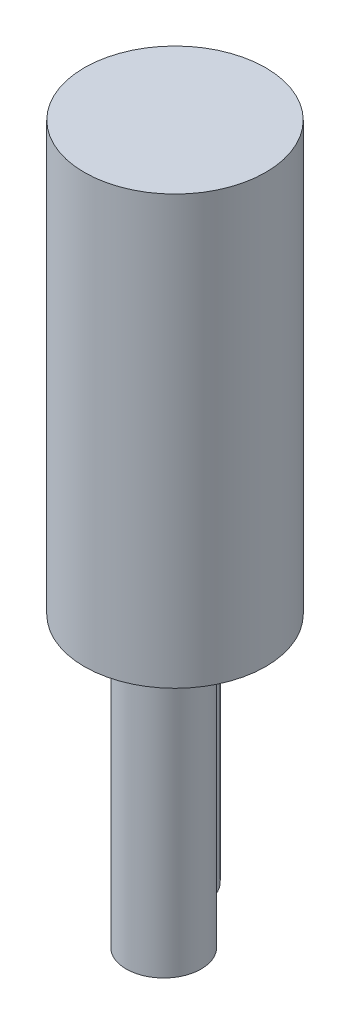
SolidWorks part; units mm, degrees
ref_plane "Front Plane" through (0, 0, 0) normal (0, 0, 1) x (1, 0, 0)
ref_plane "Top Plane" through (0, 0, 0) normal (0, 1, 0) x (1, 0, 0)
ref_plane "Right Plane" through (0, 0, 0) normal (1, 0, 0) x (0, 0, -1)
sketch "Sketch1" plane through (0, 0, 0) normal (0, 1, 0) x (1, 0, 0)
  circle A0 centre (0, 0) radius 169.5
  dimension "D1" = 339
extrude "Boss-Extrude1" add sketch "Sketch1" along normal blind 800
sketch "Sketch2" plane through (0, 0, 0) normal (0, -1, 0) x (1, 0, 0)
  line L0 (117.6839, 144.0921) -> (110.4277, 136.3525) construction
  line L1 (-142.8019, -133.7466) -> (-135.5457, -126.007) construction
  line L2 (-159.9588, 242.9996) -> (-156.7594, 246.4121) construction
  line L3 (-262.5845, 133.5372) -> (-259.3852, 136.9497) construction
  line L4 (117.6839, 144.0921) -> (110.4277, 136.3525)
  line L5 (-142.8019, -133.7466) -> (-135.5457, -126.007)
  line L6 (-159.9588, 242.9996) -> (-156.7594, 246.4121)
  line L7 (-262.5845, 133.5372) -> (-259.3852, 136.9497)
  line L8 (-367.7025, 235.2958) -> (113.1249, -215.5006) construction
  line L9 (-265.0767, 344.7582) -> (114.3717, -10.991) construction
  line L10 (-135.599, -126.0639) -> (110.4277, 136.3525) construction
  circle A0 centre (-63.8719, -49.5585) radius 70
  circle A1 centre (38.7539, 59.904) radius 70
  point P15 (-63.8719, -49.5585)
  point P21 (38.7539, 59.904)
  point P24 (-260.9849, 135.2434)
  dimension "D1" = 140
  dimension "D2" = 140
  dimension "D4" = 71.3467
extrude "Boss-Extrude2" add sketch "Sketch2" along normal blind 490 contours A0 | A1
equation "\"userHeight\"= 2000"
equation "\"hipDiameter\"= 0.191 * \"userHeight\""
equation "\"hipToKneeLength\"= ( 0.53 - 0.285 ) * \"userHeight\""
equation "\"D1@Boss-Extrude2\"=0.245*\"userHeight\""
